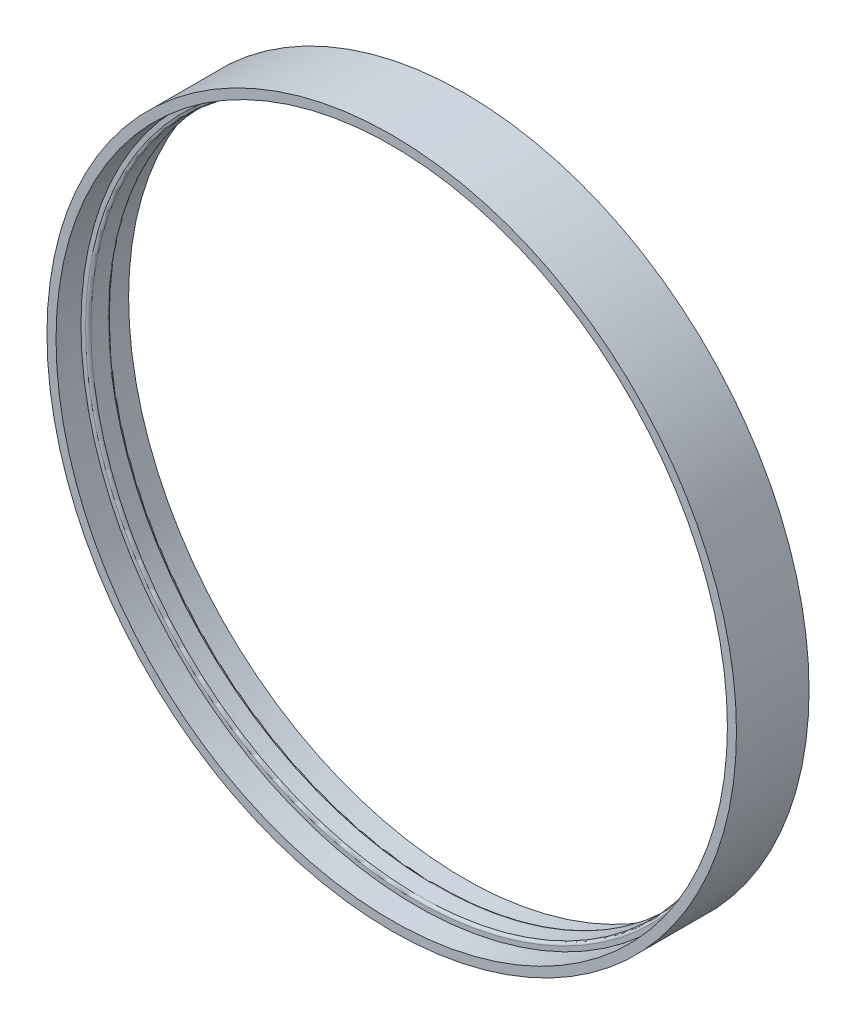
SolidWorks part; units mm, degrees
material "NBR"
ref_plane "Front Plane" through (0, 0, 0) normal (0, 0, 1) x (1, 0, 0)
ref_plane "Top Plane" through (0, 0, 0) normal (0, 1, 0) x (1, 0, 0)
ref_plane "Right Plane" through (0, 0, 0) normal (1, 0, 0) x (0, 0, -1)
sketch "Sketch2" plane through (0, 0, 0) normal (1, 0, 0) x (0, 0, -1)
  line L0 (-3.175, 93.98) -> (-3.175, 92.71)
  line L1 (-10.16, 96.52) -> (10.16, 96.52)
  line L2 (-10.16, 96.52) -> (-10.16, 93.98)
  line L3 (-10.16, 93.98) -> (-3.175, 93.98)
  line L4 (10.16, 96.52) -> (10.16, 93.98)
  line L9 (-2.413, 91.948) -> (2.413, 91.948)
  line L14 (3.175, 93.98) -> (10.16, 93.98)
  line L15 (3.175, 93.98) -> (3.175, 92.71)
  arc A0 (2.413, 91.948) -> (3.175, 92.71) centre (2.413, 92.71) ccw
  arc A1 (-3.175, 92.71) -> (-2.413, 91.948) centre (-2.413, 92.71) ccw
  point P0 (0, 0)
  point P5 (0, 91.948)
  point P7 (-2.7423, 12.3092)
  point P9 (0, 0)
  point P10 (0, 96.52)
  point P14 (3.175, 91.948)
  point P18 (-3.175, 91.948)
  dimension "D6" = 0.762
  dimension "D1" = 2.54
  dimension "D2" = 2.032
  dimension "D3" = 20.32
  dimension "D4" = 6.35
  dimension "D5" = 96.52
ref_axis "Axis1" through (0, 0, -11.176) along (0, 0, 1)
revolve "Revolve1" add sketch "Sketch2" angle 360 about axis through (0, 0, -11.176) along (0, 0, 1)
